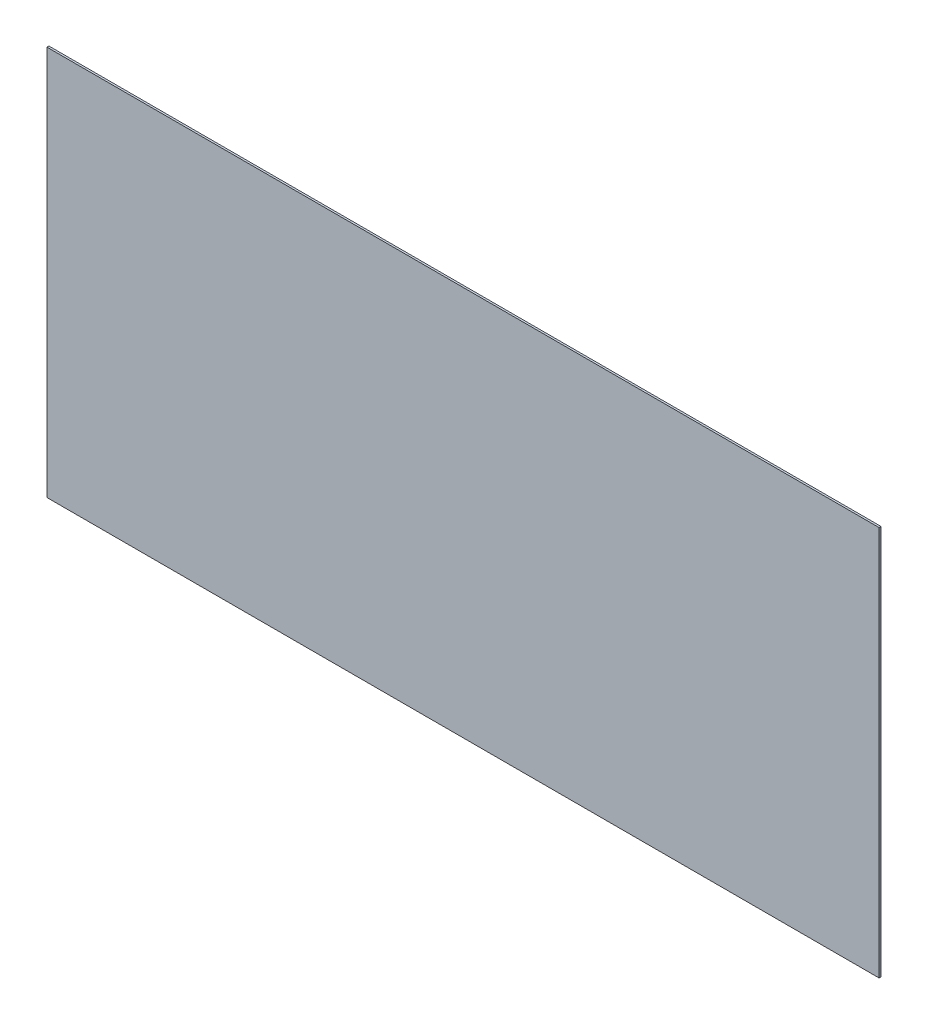
SolidWorks part; units mm, degrees
ref_plane "Front Plane" through (0, 0, 0) normal (0, 0, 1) x (1, 0, 0)
ref_plane "Top Plane" through (0, 0, 0) normal (0, 1, 0) x (1, 0, 0)
ref_plane "Right Plane" through (0, 0, 0) normal (1, 0, 0) x (0, 0, -1)
other "Configuration Table"
sketch "Sketch1" plane through (0, 0, 0) normal (0, 0, 1) x (1, 0, 0)
  line L1 (30, 300) -> (670, 300)
  line L2 (30, 300) -> (30, 600)
  line L3 (30, 600) -> (670, 600)
  line L4 (670, 300) -> (670, 600)
extrude "PACK_panel_mekanizma_1" add sketch "Sketch1" along normal blind 1.5 from offset 38.5 separate body
